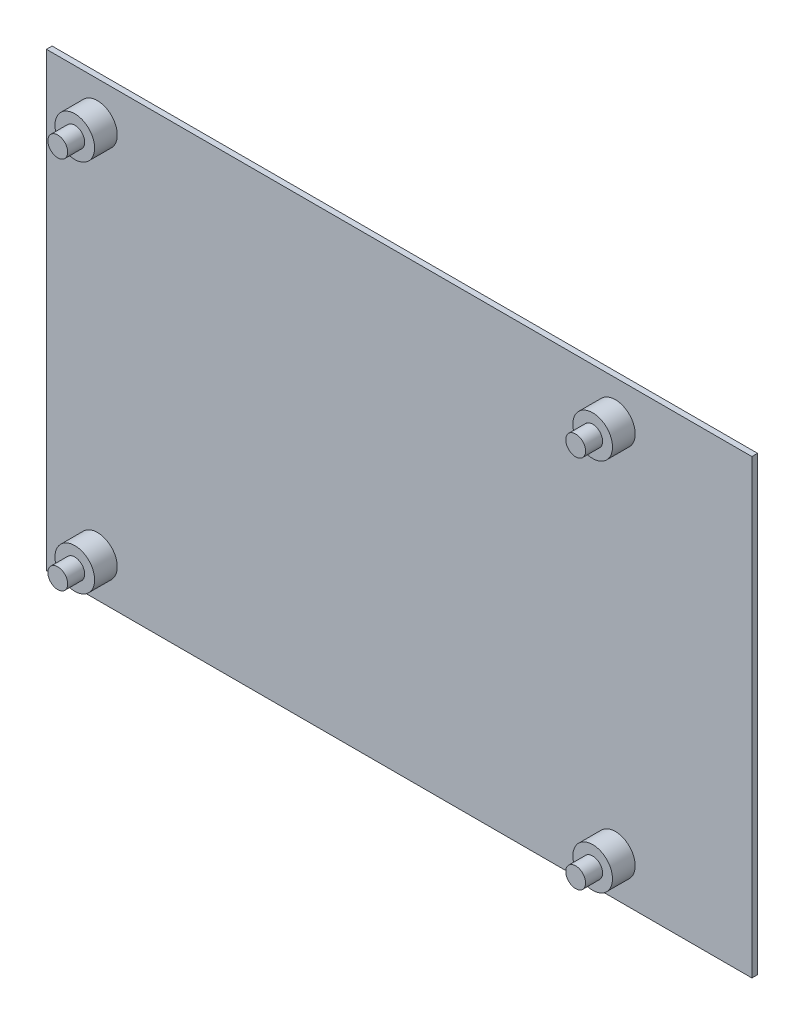
SolidWorks part; units mm, degrees
ref_plane "Front Plane" through (0, 0, 0) normal (0, 0, 1) x (1, 0, 0)
ref_plane "Top Plane" through (0, 0, 0) normal (0, 1, 0) x (1, 0, 0)
ref_plane "Right Plane" through (0, 0, 0) normal (1, 0, 0) x (0, 0, -1)
sketch "Sketch1" plane through (0, 0, 0) normal (0, 0, 1) x (1, 0, 0)
  line L0 (47.25, 21.7) -> (47.25, 23.4) construction
  line L1 (47.25, 23.4) -> (-77.25, 23.4)
  line L2 (47.25, 23.4) -> (47.25, -56.3)
  line L3 (47.25, -56.3) -> (-77.25, -56.3)
  line L4 (-77.25, 23.4) -> (-77.25, -56.3)
  line L5 (47.25, 23.4) -> (-77.25, -56.3) construction
  line L6 (47.25, -56.3) -> (-77.25, 23.4) construction
  point P0 (-15, -16.45)
  dimension "D1" = 79.7
extrude "Boss-Extrude1" add sketch "Sketch1" along normal blind 1
sketch "Sketch2" plane through (0, 0, 1) normal (0, 0, 1) x (1, 0, 0)
  line L1 (23.15, 16.55) -> (-68.25, 16.55) construction
  line L2 (23.15, 16.55) -> (23.15, -49.45) construction
  line L3 (23.15, -49.45) -> (-68.25, -49.45) construction
  line L4 (-68.25, 16.55) -> (-68.25, -49.45) construction
  line L5 (23.15, 16.55) -> (-68.25, -49.45) construction
  line L6 (23.15, -49.45) -> (-68.25, 16.55) construction
  line L7 (-77.25, 23.4) -> (-77.25, -56.3) construction
  line L8 (-49.3515, -49.45) -> (-49.3515, -56.3) construction
  line L9 (-77.25, -56.3) -> (47.25, -56.3) construction
  line L10 (-49.3515, 16.55) -> (-49.3515, 23.4) construction
  line L11 (47.25, 23.4) -> (-77.25, 23.4) construction
  circle A0 centre (-68.25, 16.55) radius 3.5
  circle A1 centre (23.15, 16.55) radius 3.5
  circle A2 centre (23.15, -49.45) radius 3.5
  circle A3 centre (-68.25, -49.45) radius 3.5
  point P0 (-22.55, -16.45)
  dimension "D4" = 7
  dimension "D1" = 91.4
  dimension "D2" = 66
  dimension "D3" = 9
extrude "Boss-Extrude2" add sketch "Sketch2" along normal blind 4
sketch "Sketch3" plane through (0, 0, 5) normal (0, 0, 1) x (1, 0, 0)
  circle A0 centre (-68.25, 16.55) radius 1.75
  circle A1 centre (23.15, 16.55) radius 1.75
  circle A2 centre (23.15, -49.45) radius 1.75
  circle A3 centre (-68.25, -49.45) radius 1.75
  dimension "D1" = 3.5
extrude "Boss-Extrude3" add sketch "Sketch3" along normal blind 3
